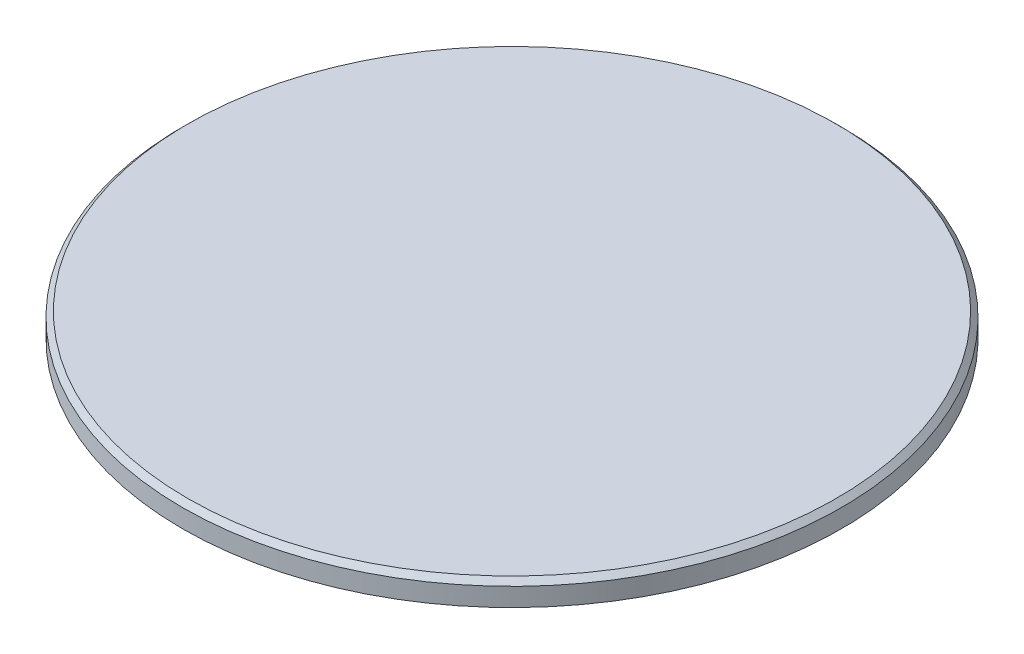
SolidWorks part; units mm, degrees
ref_plane "Front Plane" through (0, 0, 0) normal (0, 0, 1) x (1, 0, 0)
ref_plane "Top Plane" through (0, 0, 0) normal (0, 1, 0) x (1, 0, 0)
ref_plane "Right Plane" through (0, 0, 0) normal (1, 0, 0) x (0, 0, -1)
sketch "Sketch1" plane through (0, 0, 0) normal (0, 1, 0) x (1, 0, 0)
  circle A0 centre (0, 0) radius 12.55
  dimension "D1" = 25.1
extrude "Boss-Extrude1" add sketch "Sketch1" along normal blind 0.9
chamfer "Chamfer1" distance 0.2 angle 45 1 edges at (0, 0.9, 12.55)
